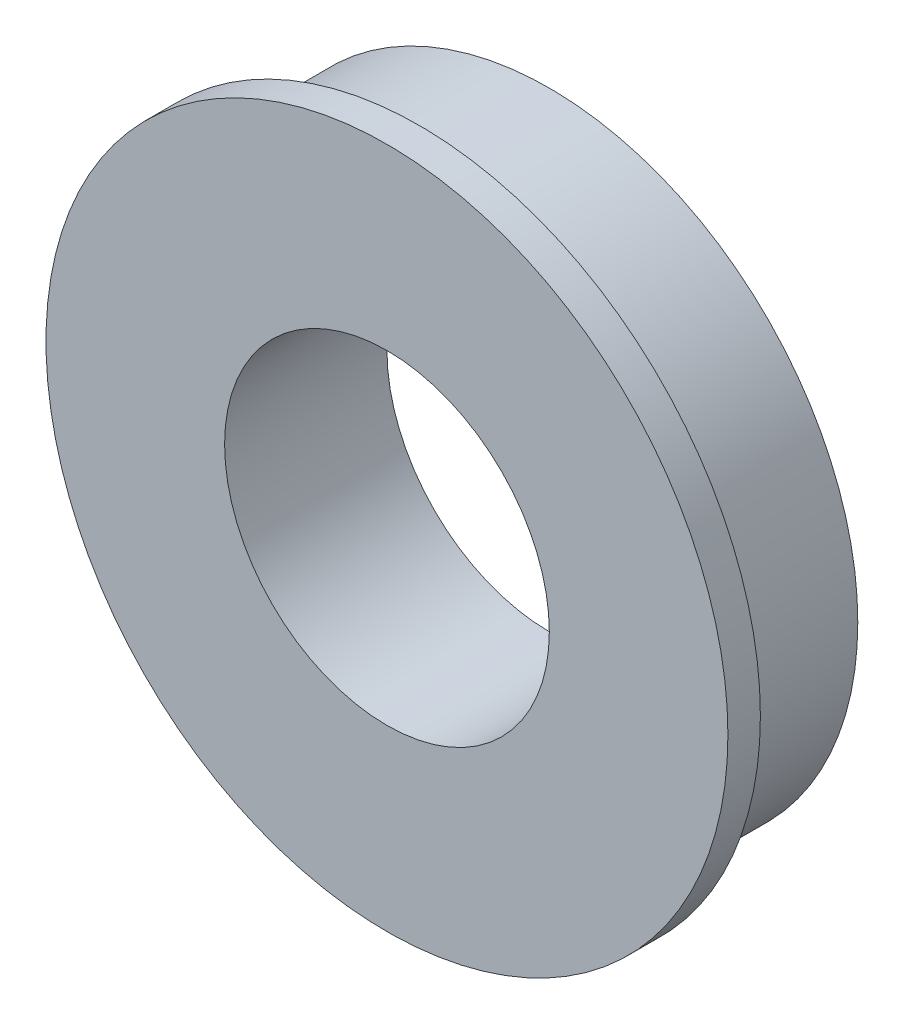
SolidWorks part; units mm, degrees
ref_plane "前视基准面" through (0, 0, 0) normal (0, 0, 1) x (1, 0, 0)
ref_plane "上视基准面" through (0, 0, 0) normal (0, 1, 0) x (1, 0, 0)
ref_plane "右视基准面" through (0, 0, 0) normal (1, 0, 0) x (0, 0, -1)
sketch "草图1" plane through (0, 0, 0) normal (0, 0, 1) x (1, 0, 0)
  circle A0 centre (0, 0) radius 9.5
  circle A1 centre (0, 0) radius 5
extrude "凸台-拉伸1" add sketch "草图1" along normal blind 4
sketch "草图2" plane through (0, 0, 4) normal (0, 0, 1) x (1, 0, 0)
  circle A0 centre (0, 0) radius 10.5
  circle A1 centre (0, 0) radius 5
  dimension "D1" = 21
extrude "凸台-拉伸2" add sketch "草图2" along normal blind 1
